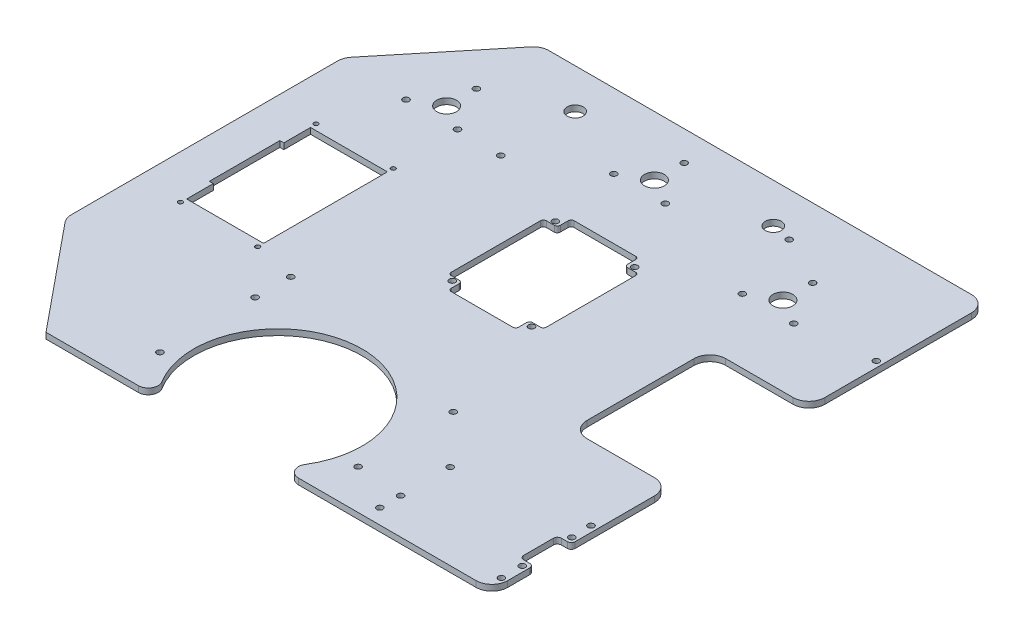
SolidWorks part; units mm, degrees
material "Thornel Mat VMA"
ref_plane "前视基准面" through (0, 0, 0) normal (0, 0, 1) x (1, 0, 0)
ref_plane "上视基准面" through (0, 0, 0) normal (0, 1, 0) x (1, 0, 0)
ref_plane "右视基准面" through (0, 0, 0) normal (1, 0, 0) x (0, 0, -1)
other "VMA"
sketch "草图1" plane through (0, 0, 0) normal (0, 1, 0) x (1, 0, 0)
  line L1 (-135, 125) -> (135, 125)
  line L2 (-135, 125) -> (-135, -125)
  line L3 (-135, -125) -> (135, -125)
  line L4 (135, 125) -> (135, -125)
  line L5 (-135, 125) -> (135, -125) construction
  line L6 (-135, -125) -> (135, 125) construction
  circle A2 centre (132, 72) radius 1.55
  circle A3 centre (132, -72) radius 1.55
  point P0 (0, 0)
  dimension "D9" = 3.1
  dimension "D10" = 3.1
  dimension "D11" = 53
  dimension "D12" = 53
  dimension "D13" = 3
  dimension "D14" = 3
  dimension "D1" = 270
  dimension "D2" = 250
extrude "凸台-拉伸1" add sketch "草图1" along normal blind 3
ref_plane "基准面1" through (0, 3, 0) normal (0, 1, 0) x (1, 0, 0)
sketch "草图2" plane through (0, 3, 0) normal (0, 1, 0) x (1, 0, 0)
  line L0 (135, -125) -> (135, 125) construction
  line L1 (-135, -125) -> (135, -125) construction
  circle A0 centre (-3, -95) radius 40
  dimension "D2" = 30
  dimension "D3" = 80
  dimension "D1" = 138
extrude "切除-拉伸1" cut sketch "草图2" against normal blind 10
sketch "草图4" plane through (0, 3, 0) normal (0, 1, 0) x (1, 0, 0)
  line L0 (-90, -125) -> (-135, -70)
  line L2 (-135, 125) -> (-135, -125) construction
  line L3 (-90, 125) -> (-135, 70)
  line L4 (135, 125) -> (-135, 125) construction
  line L5 (-90, 125) -> (-171.6981, 153.7773)
  line L6 (-171.6981, 153.7773) -> (-135, 70)
  line L7 (-90, -125) -> (-162.9767, -172.0353)
  line L8 (-162.9767, -172.0353) -> (-135, -70)
  dimension "D1" = 45
  dimension "D2" = 55
  dimension "D3" = 55
  dimension "D4" = 45
extrude "切除-拉伸3" cut sketch "草图4" against normal blind 10
sketch "草图5" plane through (0, 3, 0) normal (0, 1, 0) x (1, 0, 0)
  line L0 (135, 125) -> (-90, 125) construction
  line L2 (-3, -95) -> (-3, 125) construction
  circle A0 centre (-87.8528, 75) radius 15 construction
  circle A1 centre (-3, 95) radius 15 construction
  circle A2 centre (81.8528, 75) radius 15 construction
  circle A3 centre (-3, -95) radius 190 construction
  circle A4 centre (-87.8528, 75) radius 5
  circle A5 centre (-3, 95) radius 5
  circle A6 centre (81.8528, 75) radius 5
  circle A7 centre (-87.8528, 90) radius 1.55
  circle A8 centre (-74.8624, 67.5) radius 1.55
  circle A9 centre (-100.8432, 67.5) radius 1.55
  circle A10 centre (-3, 110) radius 1.55
  circle A11 centre (9.9904, 87.5) radius 1.55
  circle A12 centre (-15.9904, 87.5) radius 1.55
  circle A13 centre (81.8528, 90) radius 1.55
  circle A14 centre (94.8432, 67.5) radius 1.55
  circle A15 centre (68.8624, 67.5) radius 1.55
  point P23 (-87.8528, 75)
  point P32 (-3, 95)
  point P39 (81.8528, 75)
  dimension "D1" = 30
  dimension "D2" = 30
  dimension "D3" = 30
  dimension "D8" = 10
  dimension "D5" = 50
  dimension "D6" = 50
  dimension "D7" = 10
  dimension "D9" = 10
  dimension "D10" = 3.1
  dimension "D12" = 3.1
  dimension "D14" = 3.1
  dimension "D4" = 30
  dimension "D11" = 3
  dimension "D13" = 3
  dimension "D15" = 3
extrude "切除-拉伸4" cut sketch "草图5" against normal blind 10
sketch "草图6" plane through (0, 3, 0) normal (0, 1, 0) x (1, 0, 0)
  line L5 (-45.5, -147.5) -> (39.5, -42.5) construction
  line L6 (-45.5, -42.5) -> (39.5, -147.5) construction
  circle A0 centre (-3, -95) radius 42.5
  point P0 (-3, -95)
  dimension "D1" = 105
  dimension "D3" = 85
  dimension "D2" = 85
extrude "切除-拉伸5" cut sketch "草图6" against normal blind 10
sketch "草图8" plane through (0, 3, 0) normal (0, 1, 0) x (1, 0, 0)
  line L0 (135, -125) -> (135, 125) construction
  line L1 (185, 35) -> (85, 35)
  line L2 (185, 35) -> (185, -35)
  line L3 (185, -35) -> (85, -35)
  line L4 (85, 35) -> (85, -35)
  line L5 (185, 35) -> (85, -35) construction
  line L6 (185, -35) -> (85, 35) construction
  point P0 (135, 0)
  dimension "D1" = 100
  dimension "D2" = 70
extrude "切除-拉伸7" cut sketch "草图8" against normal blind 10
sketch "草图9" plane through (0, 3, 0) normal (0, 1, 0) x (1, 0, 0)
  line L0 (135, 125) -> (-90, 125) construction
  line L1 (-135, 70) -> (-135, -70) construction
  circle A0 centre (-52.5, 67) radius 1.55
  dimension "D1" = 3.1
  dimension "D2" = 58
  dimension "D3" = 82.5
extrude "切除-拉伸8" cut sketch "草图9" against normal blind 10
sketch "草图10" plane through (0, 3, 0) normal (0, 1, 0) x (1, 0, 0)
  line L0 (135, 125) -> (-90, 125) construction
  line L1 (135, 35) -> (135, 125) construction
  circle A0 centre (57, 103) radius 1.55
  dimension "D1" = 22
  dimension "D2" = 78
  dimension "D3" = 3.1
extrude "切除-拉伸9" cut sketch "草图10" against normal blind 10
sketch "草图11" plane through (0, 3, 0) normal (0, 1, 0) x (1, 0, 0)
  line L0 (-90, -125) -> (-33.104, -125) construction
  line L1 (-135, 70) -> (-135, -70) construction
  circle A0 centre (-52.5, -39) radius 1.55
  dimension "D1" = 86
  dimension "D2" = 82.5
  dimension "D3" = 3.1
extrude "切除-拉伸10" cut sketch "草图11" against normal blind 10
sketch "草图12" plane through (0, 3, 0) normal (0, 1, 0) x (1, 0, 0)
  line L0 (-135, 70) -> (-135, -70) construction
  line L1 (-115, 32.8) -> (-71.85, 32.8) construction
  line L2 (-115, 32.8) -> (-115, -32.8) construction
  line L3 (-115, -32.8) -> (-71.85, -32.8) construction
  line L4 (-71.85, 32.8) -> (-71.85, -32.8) construction
  line L5 (-115, 32.8) -> (-71.85, -32.8) construction
  line L6 (-115, -32.8) -> (-71.85, 32.8) construction
  line L7 (-135, 0) -> (85, 0) construction
  line L8 (85, 35) -> (85, -35) construction
  line L9 (-112.775, 0) -> (-73.975, 0) construction
  line L10 (-112.775, 31.25) -> (-73.975, 31.25)
  line L11 (-112.775, 31.25) -> (-112.775, -31.25)
  line L12 (-112.775, -31.25) -> (-73.975, -31.25)
  line L13 (-73.975, 31.25) -> (-73.975, -31.25)
  line L15 (-114.775, 17.8) -> (-110.775, 17.8)
  line L16 (-114.775, 17.8) -> (-114.775, -17.8)
  line L17 (-114.775, -17.8) -> (-110.775, -17.8)
  line L18 (-110.775, 17.8) -> (-110.775, -17.8)
  line L19 (-114.775, 17.8) -> (-110.775, -17.8) construction
  line L20 (-114.775, -17.8) -> (-110.775, 17.8) construction
  circle A4 centre (-73.975, -34.2) radius 1.1
  circle A5 centre (-112.975, -34.2) radius 1.1
  circle A6 centre (-73.975, 34.2) radius 1.1
  circle A7 centre (-112.975, 34.2) radius 1.1
  point P0 (-93.425, 0)
  dimension "D4" = 2.2
  dimension "D5" = 2.95
  dimension "D6" = 20.225
  dimension "D7" = 2.2
  dimension "D10" = 39
  dimension "D13" = 2.95
  dimension "D1" = 65.6
  dimension "D2" = 43.15
  dimension "D3" = 20
  dimension "D8" = 38.8
  dimension "D9" = 62.5
  dimension "D11" = 35.6
  dimension "D12" = 4
sketch "草图13" plane through (0, 3, 0) normal (0, 1, 0) x (1, 0, 0)
  line L5 (-14, 2) -> (34, 2)
  line L11 (-14, 2) -> (-14, 50)
  line L12 (-14, 50) -> (34, 50)
  line L21 (34, 2) -> (34, 50)
  line L22 (-14, 2) -> (34, 50) construction
  line L23 (-14, 50) -> (34, 2) construction
  line L24 (-7, -5) -> (27, -5)
  line L25 (-7, -5) -> (-7, 57)
  line L26 (-7, 57) -> (27, 57)
  line L27 (27, -5) -> (27, 57)
  line L28 (-7, -5) -> (27, 57) construction
  line L29 (-7, 57) -> (27, -5) construction
  line L30 (-10, 0) -> (30, 0) construction
  line L31 (-10, 0) -> (-10, 52) construction
  line L32 (-10, 52) -> (30, 52) construction
  line L33 (30, 0) -> (30, 52) construction
  line L34 (-10, 0) -> (30, 52) construction
  line L35 (-10, 52) -> (30, 0) construction
  circle A0 centre (30, 52) radius 1.55
  circle A1 centre (30, 0) radius 1.55
  circle A2 centre (-10, 0) radius 1.55
  circle A3 centre (-10, 52) radius 1.55
  point P0 (10, 26)
  point P5 (10, 26)
  point P10 (10, 26)
  dimension "D3" = 62
  dimension "D4" = 34
  dimension "D5" = 52
  dimension "D6" = 40
  dimension "D7" = 3.1
  dimension "D8" = 3.1
  dimension "D9" = 3.1
  dimension "D10" = 3.1
  dimension "D1" = 48
  dimension "D2" = 48
  dimension "D11" = 10
fillet "圆角3" radius 8 9 edges at (-90, 1.5, -125) (-135, 1.5, -70) (-135, 1.5, 70) (135, 1.5, -125) (135, 1.5, -35) (85, 1.5, -35) (85, 1.5, 35) (135, 1.5, 35) (135, 1.5, 125)
extrude "切除-拉伸12" cut sketch "草图13" against normal blind 10 contours L5 L27 L12 L25 | L27 L5 L21 L12 | L12 L27 L26 L25 | L5 L25 L12 L11 | L24 L27 L5 L25 | A1 | A3 | A2 | A0
fillet "圆角4" radius 1.5 12 edges at (-14, 1.5, -50) (-7, 1.5, -57) (27, 1.5, -57) (27, 1.5, -50) (34, 1.5, -50) (34, 1.5, -2) (27, 1.5, -2) (27, 1.5, 5) (-7, 1.5, 5) (-7, 1.5, -2) (-14, 1.5, -2) (-7, 1.5, -50)
sketch "草图15" plane through (0, 3, 0) normal (0, 1, 0) x (1, 0, 0)
  line L1 (-90, -125) -> (-33.104, -125) construction
  line L3 (27.104, -125) -> (127, -125) construction
  circle A0 centre (47.5, -105) radius 1.55
  circle A1 centre (-52.5, -105) radius 1.55
  circle A2 centre (47.5, -57) radius 1.55
  circle A3 centre (-52.5, -57) radius 1.55
  arc A4 (27.104, -125) -> (-33.104, -125) centre (-3, -95) ccw construction
  dimension "D1" = 20
  dimension "D3" = 3.1
  dimension "D4" = 3.1
  dimension "D5" = 20
  dimension "D7" = 3.1
  dimension "D8" = 48
  dimension "D9" = 3.1
  dimension "D10" = 48
  dimension "D2" = 49.5
  dimension "D6" = 50.5
extrude "切除-拉伸13" cut sketch "草图15" against normal blind 10
sketch "草图16" plane through (0, 0, 0) normal (0, -1, 0) x (1, 0, 0)
  line L0 (127, -125) -> (-86.209, -125) construction
  circle A0 centre (-53, -105) radius 4.05
  circle A1 centre (-3, -95) radius 5 construction
  dimension "D1" = 8.1
  dimension "D3" = 50
  dimension "D2" = 20
extrude "切除-拉伸14" cut sketch "草图16" against normal blind 10
sketch "草图19" plane through (0, 3, 0) normal (0, 1, 0) x (1, 0, 0)
  line L0 (-3, 95) -> (-3, 100) construction
  circle A0 centre (-53, 105) radius 4.05
  circle A1 centre (-3, 95) radius 5 construction
  circle A2 centre (47, 105) radius 4.05
extrude "切除-拉伸19" cut sketch "草图19" against normal blind 10
ref_plane "基准面2" through (0, 0, 0) normal (0, -1, 0) x (-1, 0, 0)
ref_plane "基准面3" through (0, 0, 0) normal (0, -1, 0) x (-1, 0, 0)
sketch "草图21" plane through (0, 0, 0) normal (0, -1, 0) x (-1, 0, 0)
  line L0 (-27.104, -125) -> (-127, -125) construction
  line L1 (-132.26, -81.94) -> (-70.88, -81.94) construction
  line L2 (-132.26, -81.94) -> (-132.26, -117.45) construction
  line L3 (-132.26, -117.45) -> (-70.88, -117.45) construction
  line L4 (-70.88, -81.94) -> (-70.88, -117.45) construction
  line L5 (-132.26, -81.94) -> (-70.88, -117.45) construction
  line L6 (-132.26, -117.45) -> (-70.88, -81.94) construction
  line L7 (-135, -117) -> (-135, -43) construction
  circle A0 centre (-132.26, -117.45) radius 1.55
  circle A1 centre (-70.88, -117.45) radius 1.55
  circle A2 centre (-70.88, -81.94) radius 1.55
  circle A3 centre (-132.26, -81.94) radius 1.55
  point P0 (-101.57, -99.695)
  dimension "D5" = 3.1
  dimension "D6" = 3.1
  dimension "D7" = 3.1
  dimension "D8" = 3.1
  dimension "D1" = 7.55
  dimension "D2" = 2.74
  dimension "D3" = 61.38
  dimension "D4" = 35.51
extrude "切除-拉伸20" cut sketch "草图21" against normal blind 10
ref_plane "基准面4" through (0, 0, 0) normal (0, -1, 0) x (-1, 0, 0)
sketch "草图23" plane through (0, 0, 0) normal (0, -1, 0) x (-1, 0, 0)
  line L0 (-135, -117) -> (-135, -43) construction
  line L1 (-135, -84.94) -> (-128, -84.94)
  line L2 (-135, -84.94) -> (-135, -103.94)
  line L3 (-135, -103.94) -> (-128, -103.94)
  line L4 (-128, -84.94) -> (-128, -103.94)
  circle A0 centre (-132.26, -81.94) radius 1.55 construction
  dimension "D3" = 3
  dimension "D1" = 19
  dimension "D2" = 7
extrude "切除-拉伸22" cut sketch "草图23" against normal blind 10
fillet "圆角8" radius 2 4 edges at (135, 1.5, 103.94) (135, 1.5, 84.94) (128, 1.5, 84.94) (128, 1.5, 103.94)
extrude "切除-拉伸23" cut sketch "草图12" against normal blind 10 contours L16 L17 L11 L15 | L18 L15 L11 L17 | L15 L18 L17 L11 L12 L13 L10 | A7 | A6 | A5 | A4
fillet "圆角9" radius 5 2 edges at (27.104, 1.5, 125) (-33.104, 1.5, 125)
ref_plane "基准面6" through (0, 3, 0) normal (0, 1, 0) x (1, 0, 0)
sketch "草图26" plane through (0, 0, 0) normal (0, -1, 0) x (-1, 0, 0)
  line L0 (-135, -117) -> (-135, -105.94) construction
  line L1 (-37.3887, -125) -> (-127, -125) construction
  circle A0 centre (-132.26, -106.94) radius 1.55
  circle A1 centre (-132.26, -81.94) radius 1.55 construction
  circle A2 centre (-70.88, -106.94) radius 1.55
  dimension "D1" = 3.1
  dimension "D2" = 25
  dimension "D3" = 2.74
  dimension "D4" = 61.38
  dimension "D5" = 3.1
  dimension "D6" = 18.06
extrude "切除-拉伸24" cut sketch "草图26" against normal blind 8
